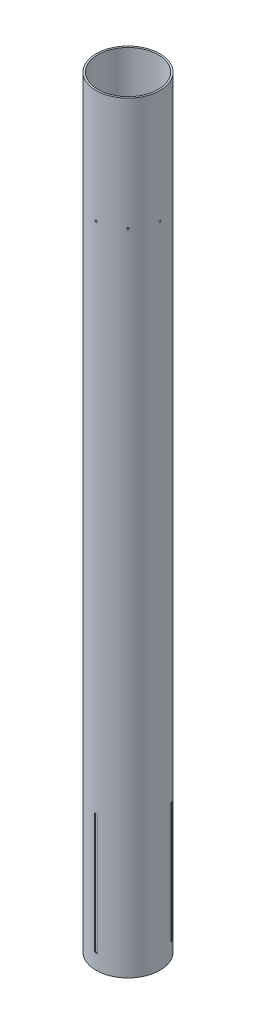
SolidWorks part; units mm, degrees
ref_plane "Front Plane" through (0, 0, 0) normal (0, 0, 1) x (1, 0, 0)
ref_plane "Top Plane" through (0, 0, 0) normal (0, 1, 0) x (1, 0, 0)
ref_plane "Right Plane" through (0, 0, 0) normal (1, 0, 0) x (0, 0, -1)
sketch "Sketch1" plane through (0, 0, 0) normal (0, 1, 0) x (1, 0, 0)
  circle A0 centre (0, 0) radius 53.721
  circle A1 centre (0, 0) radius 50.8
  dimension "D1" = 107.442
  dimension "D2" = 101.6
extrude "Tube Extrusion" add sketch "Sketch1" along normal blind 1282.7
ref_plane "Plane1" through (0, 0, 53.721) normal (0, 0, 1) x (1, 0, 0)
sketch "Sketch2" plane through (0, 0, 53.721) normal (0, 0, 1) x (1, 0, 0)
  line L0 (0, 1282.7) -> (0, 0) construction
  line L3 (53.721, 1282.7) -> (-53.721, 1282.7) construction
  circle A0 centre (0, 1092.2) radius 1.6383
  dimension "D1" = 3.2766
  dimension "D2" = 1092.2
extrude "Engine Block Hole" cut sketch "Sketch2" against normal up to next
pattern_circular "CirPattern1" count 8 over 360 about axis through (0, 1282.7, 0) along (0, -1, 0) of "Engine Block Hole"
sketch "Sketch3" plane through (0, 0, 53.721) normal (0, 0, 1) x (1, 0, 0)
  line L0 (0, 0) -> (0, 25.4) construction
  line L1 (-53.721, 0) -> (53.721, 0) construction
  line L3 (-2.667, 228.6) -> (2.667, 228.6)
  line L4 (-2.667, 228.6) -> (-2.667, 25.4)
  line L5 (-2.667, 25.4) -> (2.667, 25.4)
  line L6 (2.667, 228.6) -> (2.667, 25.4)
  point P8 (0, 25.4)
  dimension "D1" = 25.4
  dimension "D2" = 203.2
  dimension "D3" = 5.334
extrude "Fin Slots" cut sketch "Sketch3" against normal blind 1.27
pattern_circular "CirPattern2" count 3 over 360 about axis through (0, 0, 0) along (0, 1, 0) of "Fin Slots"
